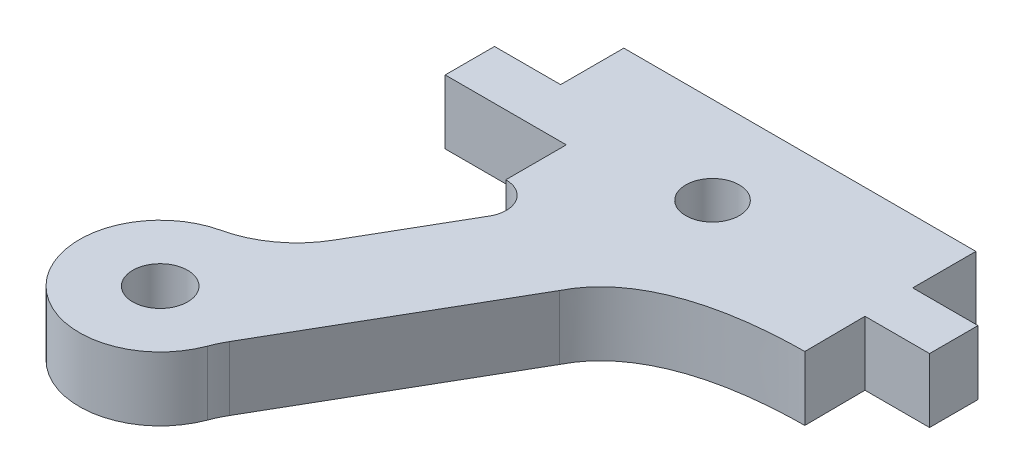
SolidWorks part; units mm, degrees
ref_plane "Front Plane" through (0, 0, 0) normal (0, 0, 1) x (1, 0, 0)
ref_plane "Top Plane" through (0, 0, 0) normal (0, 1, 0) x (1, 0, 0)
ref_plane "Right Plane" through (0, 0, 0) normal (1, 0, 0) x (0, 0, -1)
sketch "Sketch1" plane through (0, 0, 0) normal (0, 1, 0) x (1, 0, 0)
  line L0 (107.779, 111.4027) -> (109.6663, 109.5428) construction
  line L1 (107.9202, 109.5441) -> (109.7803, 111.4315) construction
  line L2 (112.7229, 126.5933) -> (112.7228, 123.5932)
  line L3 (112.7229, 126.5933) -> (106.7229, 126.5933)
  line L4 (118.8037, 120.1758) -> (112.8178, 109.8083)
  line L5 (113.863, 121.6183) -> (111.0506, 116.7472)
  line L6 (106.7229, 129.0364) -> (106.7229, 126.5933)
  line L7 (106.7229, 129.0364) -> (109.9976, 129.0364)
  line L8 (109.9976, 129.0364) -> (109.9976, 132.1682)
  line L9 (109.9976, 132.1682) -> (127.44, 132.1682)
  line L10 (127.44, 129.0364) -> (127.44, 132.1682)
  line L11 (130.6758, 129.0364) -> (127.44, 129.0364)
  line L12 (130.6758, 129.0364) -> (130.6758, 126.6364)
  line L13 (130.6758, 126.6364) -> (127.476, 126.6364)
  line L14 (127.476, 126.6364) -> (127.4976, 123.6364)
  line L15 (117.7795, 128.7665) -> (119.667, 126.9064) construction
  line L16 (119.6532, 128.825) -> (117.7931, 126.9375) construction
  line L17 (118.7232, 127.8364) -> (131.8632, 127.8364) construction
  circle A0 centre (108.7226, 110.4728) radius 1.36
  arc A1 (107.8328, 114.3725) -> (112.4672, 109.0663) centre (108.7226, 110.4728) ccw
  arc A2 (112.4672, 109.0663) -> (112.8178, 109.8083) centre (117.1479, 107.3083) cw
  arc A3 (107.8328, 114.3725) -> (111.0506, 116.7472) centre (106.7205, 119.2472) ccw
  arc A4 (112.7228, 123.5932) -> (113.863, 121.6183) centre (112.7468, 122.2905) cw
  circle A5 centre (118.7232, 127.8364) radius 1.325
  spline S105 degree 3 poles (118.8037, 120.1758) (120.3618, 123.2696) (125.0558, 123.6186) (127.4976, 123.6364) knots 0.666667 0.666667 0.666667 0.666667 0.708333 0.708333 0.708333 0.708333
  dimension "D1" = 2.72
  dimension "D2" = 8
  dimension "D3" = 5
  dimension "D4" = 1.2
  dimension "D8" = 1.2
  dimension "D9" = 1.2
extrude "Boss-Extrude1" add sketch "Sketch1" along normal blind 3.175
